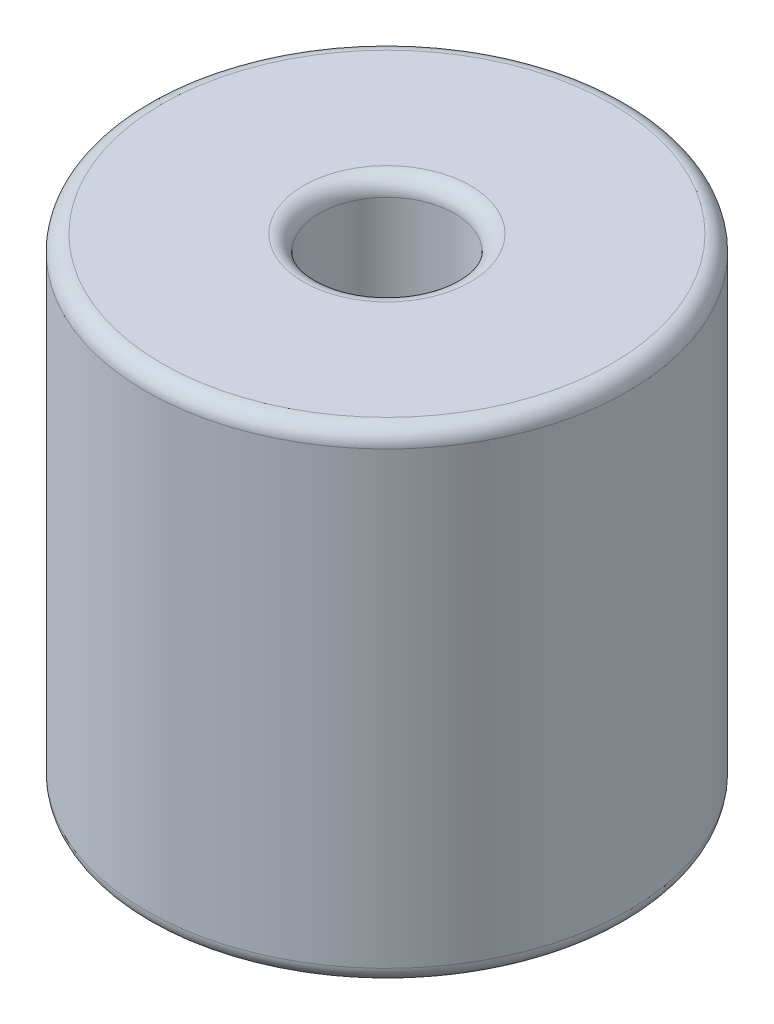
SolidWorks part; units mm, degrees
ref_plane "Front Plane" through (0, 0, 0) normal (0, 0, 1) x (1, 0, 0)
ref_plane "Top Plane" through (0, 0, 0) normal (0, 1, 0) x (1, 0, 0)
ref_plane "Right Plane" through (0, 0, 0) normal (1, 0, 0) x (0, 0, -1)
sketch "Sketch1" plane through (0, 0, 0) normal (0, 1, 0) x (1, 0, 0)
  circle A0 centre (0, 0) radius 2.1
  circle A1 centre (0, 0) radius 7.5
  dimension "D1" = 4.2
  dimension "D2" = 15
extrude "Boss-Extrude1" add sketch "Sketch1" along normal blind 15
fillet "Fillet1" radius 0.5 4 edges at (0, 0, 2.1) (0, 15, 2.1) (0, 0, 7.5) (0, 15, 7.5)
